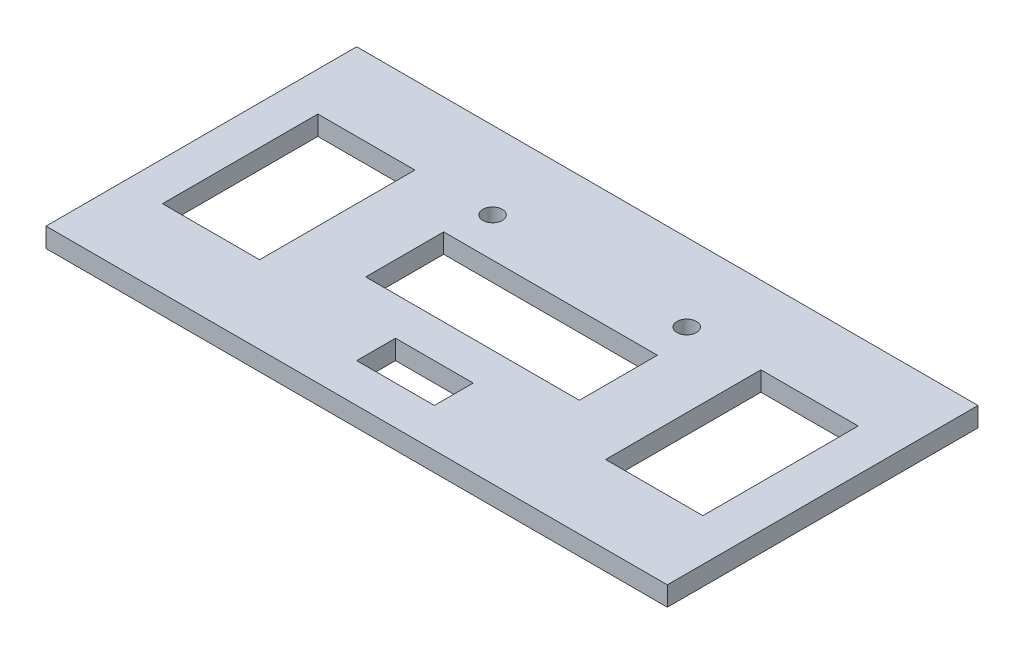
SolidWorks part; units mm, degrees
ref_plane "Front Plane" through (0, 0, 0) normal (0, 0, 1) x (1, 0, 0)
ref_plane "Top Plane" through (0, 0, 0) normal (0, 1, 0) x (1, 0, 0)
ref_plane "Right Plane" through (0, 0, 0) normal (1, 0, 0) x (0, 0, -1)
sketch "Sketch2" plane through (0, 0, 0) normal (0, 1, 0) x (1, 0, 0)
  line L1 (0, 0) -> (203.2, 0)
  line L2 (0, 0) -> (0, 101.6)
  line L3 (0, 101.6) -> (203.2, 101.6)
  line L4 (203.2, 0) -> (203.2, 101.6)
  line L9 (12.7, 76.2) -> (44.45, 76.2)
  line L10 (12.7, 76.2) -> (12.7, 25.4)
  line L11 (12.7, 25.4) -> (44.45, 25.4)
  line L12 (44.45, 76.2) -> (44.45, 25.4)
  line L13 (189.4164, 76.2) -> (157.6074, 76.2)
  line L14 (189.4164, 76.2) -> (189.4164, 25.4)
  line L15 (189.4164, 25.4) -> (157.6074, 25.4)
  line L16 (157.6074, 76.2) -> (157.6074, 25.4)
  dimension "D1" = 203.2
  dimension "D2" = 101.6
  dimension "D3" = 31.75
extrude "Boss-Extrude1" add sketch "Sketch2" along normal blind 6.35
sketch "Sketch3" plane through (0, 6.35, 0) normal (0, 1, 0) x (1, 0, 0)
  circle A0 centre (69.85, 76.2) radius 3.175
  circle A1 centre (133.35, 76.2) radius 3.175
  point P4 (0, 0)
extrude "Cut-Extrude1" cut sketch "Sketch3" against normal blind 34.544
sketch "Sketch5" plane through (0, 6.35, 0) normal (0, 1, 0) x (1, 0, 0)
  line L0 (66.6674, 63.3959) -> (66.6674, 37.8868)
  line L1 (66.6674, 63.3959) -> (136.5422, 63.3959)
  line L2 (66.6674, 37.8868) -> (136.5422, 37.8868)
  line L3 (136.5422, 63.3959) -> (136.5422, 37.8868)
extrude "Cut-Extrude2" cut sketch "Sketch5" against normal blind 34.544 contours L1 L3 L2 L0
sketch "Sketch6" plane through (0, 6.35, 0) normal (0, 1, 0) x (1, 0, 0)
  line L1 (88.9, 25.4) -> (114.3, 25.4)
  line L2 (88.9, 25.4) -> (88.9, 12.7)
  line L3 (88.9, 12.7) -> (114.3, 12.7)
  line L4 (114.3, 25.4) -> (114.3, 12.7)
  dimension "D1" = 25.4
  dimension "D2" = 12.7
extrude "Cut-Extrude3" cut sketch "Sketch6" against normal blind 34.544
